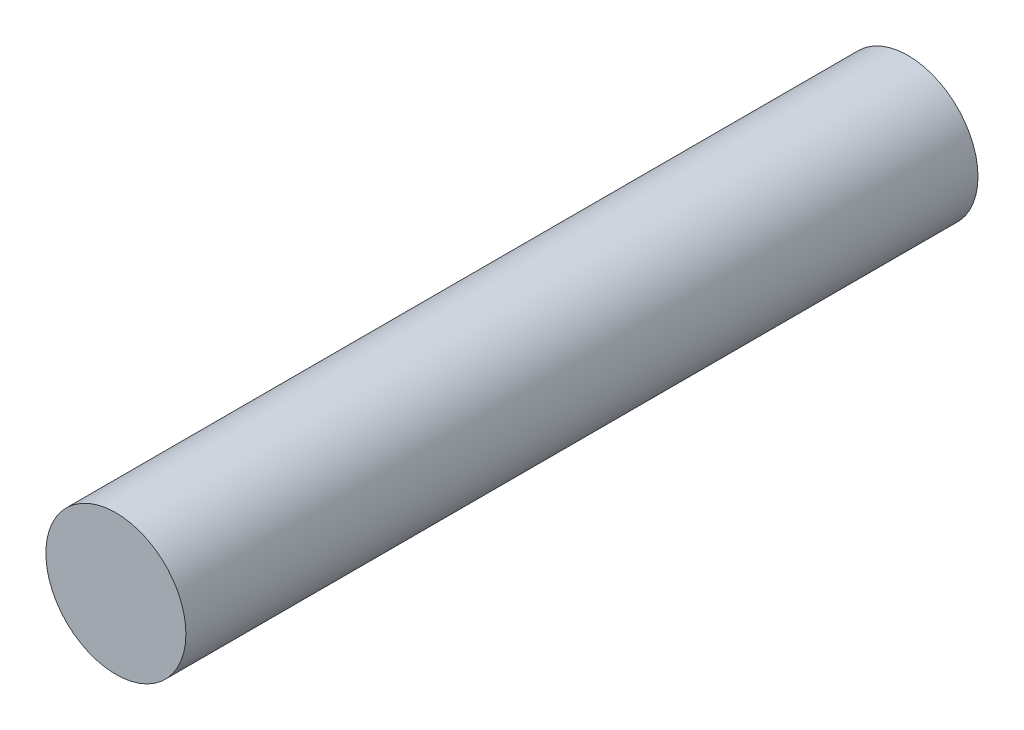
SolidWorks part; units mm, degrees
material "6061 Alloy"
ref_plane "Front Plane" through (0, 0, 0) normal (0, 0, 1) x (1, 0, 0)
ref_plane "Top Plane" through (0, 0, 0) normal (0, 1, 0) x (1, 0, 0)
ref_plane "Right Plane" through (0, 0, 0) normal (1, 0, 0) x (0, 0, -1)
sketch "Sketch1" plane through (0, 0, 0) normal (0, 0, 1) x (1, 0, 0)
  circle A0 centre (0, 0) radius 3
  dimension "D1" = 6
extrude "Boss-Extrude1" add sketch "Sketch1" along normal blind 33.9395
